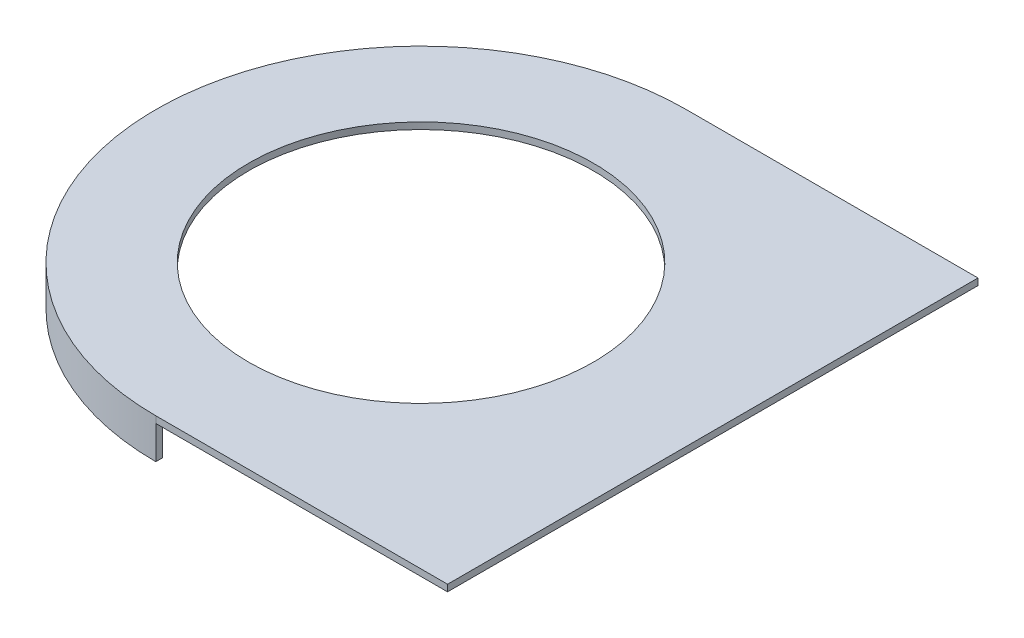
SolidWorks part; units mm, degrees
material "1060-H16"
ref_plane "前视基准面" through (0, 0, 0) normal (0, 0, 1) x (1, 0, 0)
ref_plane "上视基准面" through (0, 0, 0) normal (0, 1, 0) x (1, 0, 0)
ref_plane "右视基准面" through (0, 0, 0) normal (1, 0, 0) x (0, 0, -1)
sketch "草图1" plane through (0, 0, 0) normal (0, 1, 0) x (1, 0, 0)
  line L1 (0, 20) -> (22, 20)
  line L2 (0, 20) -> (0, -20)
  line L3 (0, -20) -> (22, -20)
  line L4 (22, 20) -> (22, -20)
  circle A0 centre (0, 0) radius 20
  dimension "D1" = 40
  dimension "D2" = 22
  dimension "D3" = 40
extrude "凸台-拉伸1" add sketch "草图1" along normal blind 0.5 contours L2 A0 | L2 A0 | A0 L3 L4 L1
sketch "草图2" plane through (0, 0, 0) normal (0, -1, 0) x (1, 0, 0)
  line L0 (0, 21.3249) -> (0, -22.4839)
  circle A0 centre (0, 0) radius 20
  circle A1 centre (0, 0) radius 19.5
  arc M1 (0, 20) -> (0, -20) centre (0, 0) ccw
  dimension "D1" = 39
  dimension "D2" = 40
extrude "凸台-拉伸2" add sketch "草图2" along normal blind 2.5 contours A1 L0 M1 | A0
sketch "草图3" plane through (0, 0.5, 0) normal (0, 1, 0) x (1, 0, 0)
  circle A0 centre (0, 0) radius 13
  dimension "D1" = 26
extrude "切除-拉伸1" cut sketch "草图3" against normal through all contours A0
